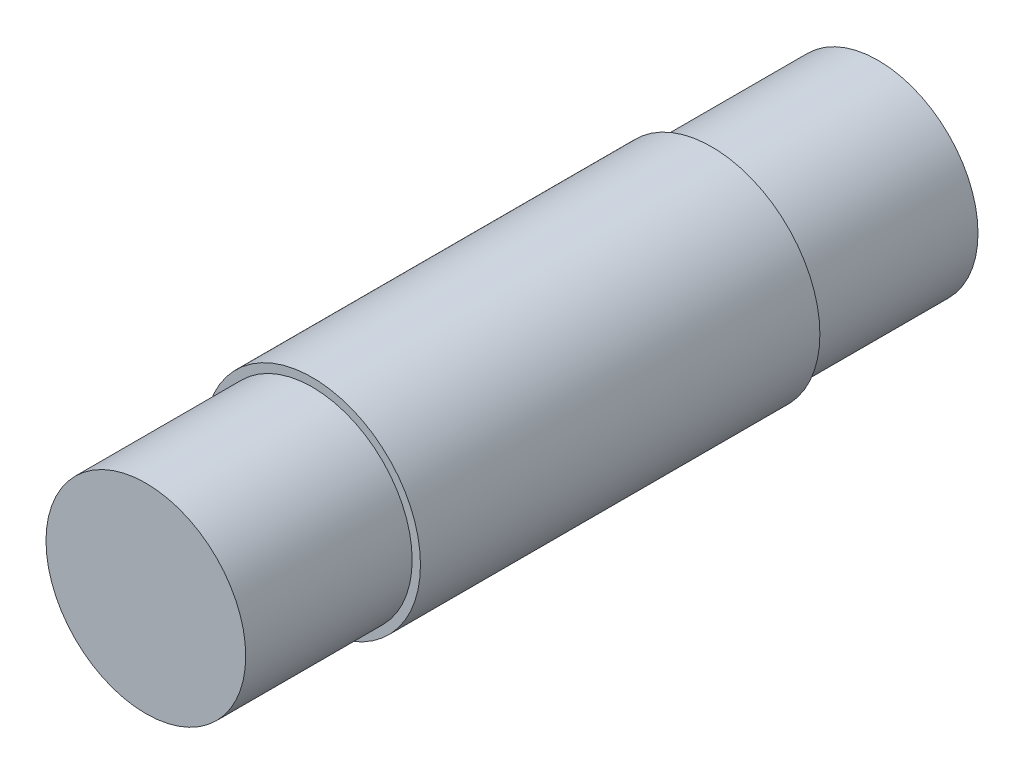
SolidWorks part; units mm, degrees
ref_plane "正面" through (0, 0, 0) normal (0, 0, 1) x (1, 0, 0)
ref_plane "平面" through (0, 0, 0) normal (0, 1, 0) x (1, 0, 0)
ref_plane "右側面" through (0, 0, 0) normal (1, 0, 0) x (0, 0, -1)
sketch "ｽｹｯﾁ1" plane through (0, 0, 0) normal (0, 0, 1) x (1, 0, 0)
  circle A0 centre (0, 0) radius 3
  dimension "D1" = 6
extrude "ﾎﾞｽ - 押し出し1" add sketch "ｽｹｯﾁ1" along normal blind 5
sketch "ｽｹｯﾁ2" plane through (0, 0, 5) normal (0, 0, 1) x (1, 0, 0)
  circle A0 centre (0, 0) radius 3.25
  dimension "D1" = 6.5
extrude "ﾎﾞｽ - 押し出し2" add sketch "ｽｹｯﾁ2" along normal blind 12
sketch "ｽｹｯﾁ3" plane through (0, 0, 17) normal (0, 0, 1) x (1, 0, 0)
  circle A0 centre (0, 0) radius 3
  dimension "D1" = 6
extrude "ﾎﾞｽ - 押し出し3" add sketch "ｽｹｯﾁ3" along normal blind 5
